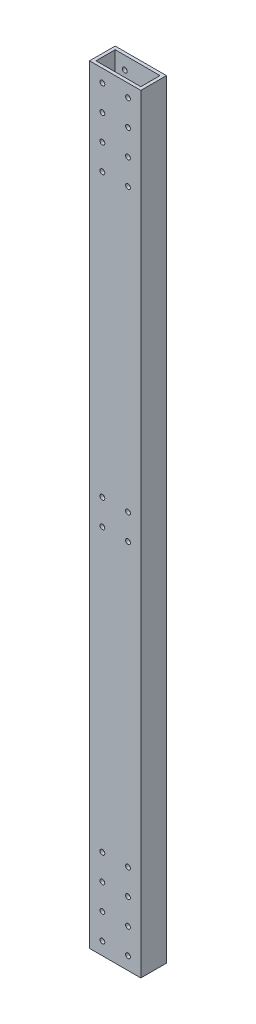
SolidWorks part; units mm, degrees
ref_plane "Front Plane" through (0, 0, 0) normal (0, 0, 1) x (1, 0, 0)
ref_plane "Top Plane" through (0, 0, 0) normal (0, 1, 0) x (1, 0, 0)
ref_plane "Right Plane" through (0, 0, 0) normal (1, 0, 0) x (0, 0, -1)
sketch "Sketch1" plane through (0, 0, 0) normal (0, 1, 0) x (1, 0, 0)
  line L1 (25.4, 12.7) -> (-25.4, 12.7)
  line L2 (25.4, 12.7) -> (25.4, -12.7)
  line L3 (25.4, -12.7) -> (-25.4, -12.7)
  line L4 (-25.4, 12.7) -> (-25.4, -12.7)
  line L5 (0, -12.7) -> (0, 12.7) construction
  line L6 (25.4, 0) -> (-25.4, 0) construction
  point P0 (0, 0)
  dimension "D1" = 50.8
  dimension "D2" = 25.4
extrude "Boss-Extrude1" add sketch "Sketch1" along normal mid plane 762
shell "Shell1" thickness 3.175
sketch "Sketch5" plane through (0, 0, 12.7) normal (0, 0, 1) x (1, 0, 0)
  line L0 (-25.4, 381) -> (25.4, 381) construction
  line L1 (12.7, 368.3) -> (-12.7, 368.3) construction
  line L2 (12.7, 368.3) -> (12.7, 342.9) construction
  line L3 (12.7, 342.9) -> (-12.7, 342.9) construction
  line L4 (-12.7, 368.3) -> (-12.7, 342.9) construction
  line L5 (0, 342.9) -> (0, 368.3) construction
  line L6 (12.7, 355.6) -> (-12.7, 355.6) construction
  line L7 (0, 0) -> (50000, 0) construction
  line L8 (12.7, -355.6) -> (-12.7, -355.6) construction
  line L9 (0, -342.9) -> (0, -368.3) construction
  line L10 (-12.7, -368.3) -> (-12.7, -342.9) construction
  line L11 (12.7, -342.9) -> (-12.7, -342.9) construction
  line L12 (12.7, -368.3) -> (12.7, -342.9) construction
  line L13 (12.7, -368.3) -> (-12.7, -368.3) construction
  line L14 (12.7, 317.5) -> (-12.7, 317.5) construction
  line L15 (12.7, 317.5) -> (12.7, 292.1) construction
  line L16 (12.7, 292.1) -> (-12.7, 292.1) construction
  line L17 (-12.7, 317.5) -> (-12.7, 292.1) construction
  line L18 (0, 292.1) -> (0, 317.5) construction
  line L19 (12.7, 304.8) -> (-12.7, 304.8) construction
  line L20 (0, 355.6) -> (0, 304.8) construction
  line L21 (12.7, -304.8) -> (-12.7, -304.8) construction
  line L22 (0, -292.1) -> (0, -317.5) construction
  line L23 (-12.7, -317.5) -> (-12.7, -292.1) construction
  line L24 (12.7, -292.1) -> (-12.7, -292.1) construction
  line L25 (12.7, -317.5) -> (12.7, -292.1) construction
  line L26 (12.7, -317.5) -> (-12.7, -317.5) construction
  circle A0 centre (-12.7, 368.3) radius 2.3813
  circle A1 centre (12.7, 368.3) radius 2.3813
  circle A2 centre (12.7, 342.9) radius 2.3813
  circle A3 centre (-12.7, 342.9) radius 2.3813
  circle A4 centre (-12.7, -342.9) radius 2.3813
  circle A5 centre (12.7, -342.9) radius 2.3813
  circle A6 centre (12.7, -368.3) radius 2.3813
  circle A7 centre (-12.7, -368.3) radius 2.3813
  circle A8 centre (-12.7, 12.7) radius 2.3813
  circle A9 centre (12.7, 12.7) radius 2.3813
  circle A10 centre (12.7, -12.7) radius 2.3813
  circle A11 centre (-12.7, -12.7) radius 2.3813
  circle A12 centre (-12.7, 317.5) radius 2.3813
  circle A13 centre (12.7, 317.5) radius 2.3813
  circle A14 centre (12.7, 292.1) radius 2.3813
  circle A15 centre (-12.7, 292.1) radius 2.3813
  circle A16 centre (-12.7, -292.1) radius 2.3813
  circle A17 centre (12.7, -292.1) radius 2.3813
  circle A18 centre (12.7, -317.5) radius 2.3813
  circle A19 centre (-12.7, -317.5) radius 2.3813
  point P8 (0, 355.6)
  point P27 (0, -355.6)
  point P45 (0, 304.8)
  point P66 (0, -304.8)
  dimension "D1" = 4.7625
  dimension "D2" = 25.4
  dimension "D3" = 12.7
  dimension "D4" = 25.4
  dimension "D6" = 50.8
  dimension "D5" = 2
extrude "Cut-Extrude2" cut sketch "Sketch5" against normal through all both
